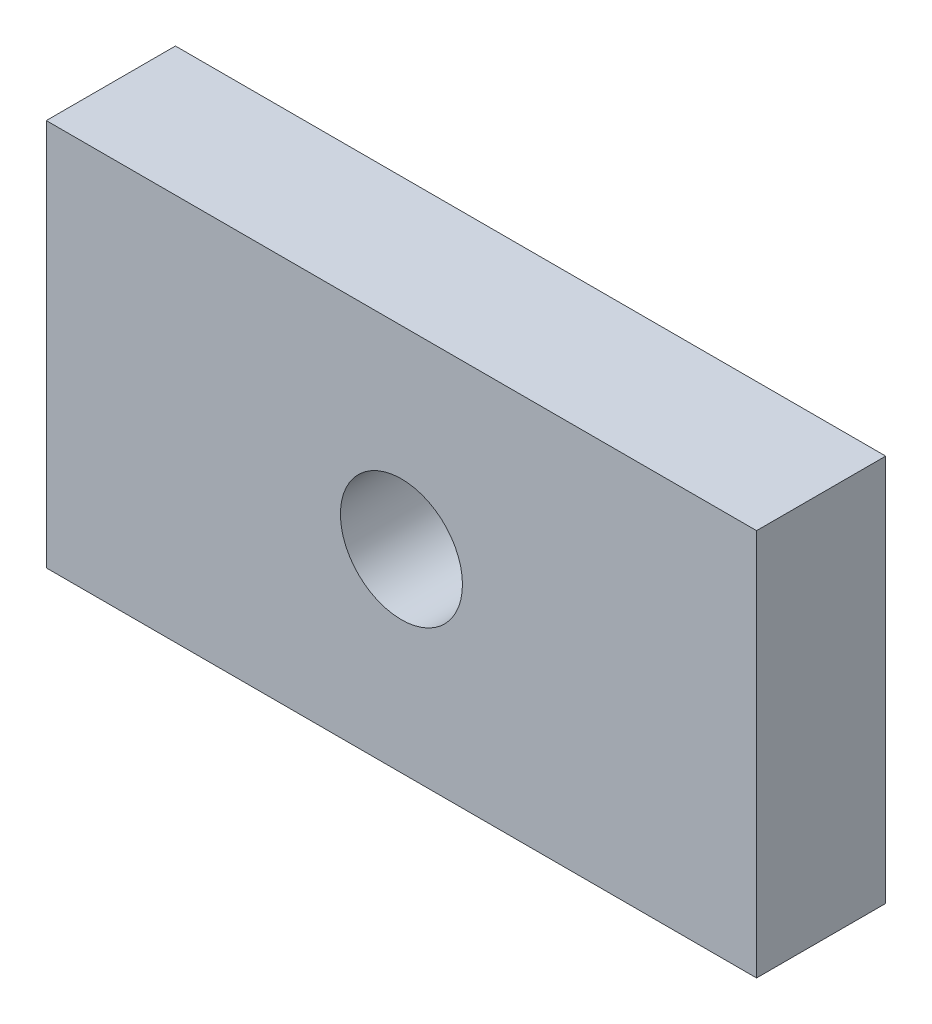
SolidWorks part; units mm, degrees
ref_plane "Front" through (0, 0, 0) normal (0, 0, 1) x (1, 0, 0)
ref_plane "Top" through (0, 0, 0) normal (0, 1, 0) x (1, 0, 0)
ref_plane "Right" through (0, 0, 0) normal (1, 0, 0) x (0, 0, -1)
sketch "Skizze1" plane through (0, 0, 0) normal (0, 0, 1) x (1, 0, 0)
  line L1 (-55, -30) -> (55, -30)
  line L2 (-55, -30) -> (-55, 30)
  line L3 (-55, 30) -> (55, 30)
  line L4 (55, -30) -> (55, 30)
  line L5 (-55, -30) -> (55, 30) construction
  line L6 (-55, 30) -> (55, -30) construction
  circle A0 centre (0, 0) radius 9.4506
  point P0 (0, 0)
  dimension "D1" = 110
  dimension "D2" = 60
extrude "Aufsatz-Linear austragen1" add sketch "Skizze1" along normal blind 20
